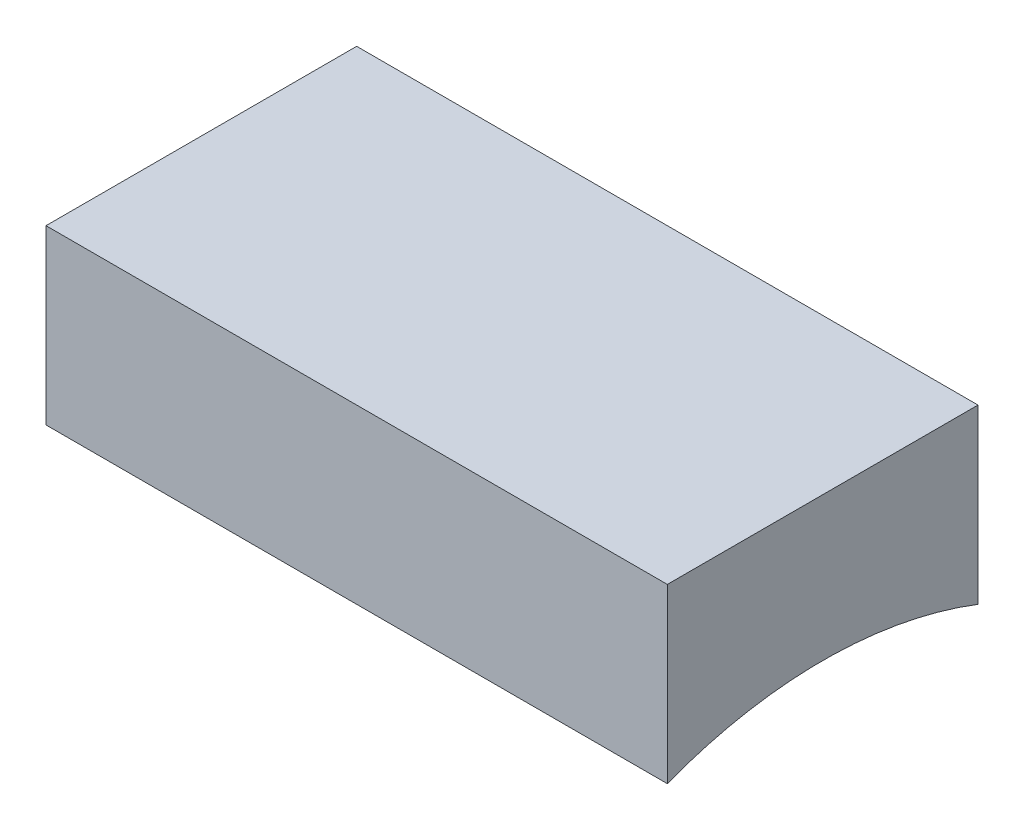
SolidWorks part; units mm, degrees
ref_plane "Front" through (0, 0, 0) normal (0, 0, 1) x (1, 0, 0)
ref_plane "Top" through (0, 0, 0) normal (0, 1, 0) x (1, 0, 0)
ref_plane "Right" through (0, 0, 0) normal (1, 0, 0) x (0, 0, -1)
sketch "Sketch1" plane through (0, 0, 0) normal (0, 1, 0) x (1, 0, 0)
  line L1 (-9, -4.5) -> (9, -4.5)
  line L2 (-9, -4.5) -> (-9, 4.5)
  line L3 (-9, 4.5) -> (9, 4.5)
  line L4 (9, -4.5) -> (9, 4.5)
  line L5 (-9, -4.5) -> (9, 4.5) construction
  line L6 (-9, 4.5) -> (9, -4.5) construction
  point P0 (0, 0)
  dimension "D1" = 9
  dimension "D2" = 18
extrude "Boss-Extrude1" add sketch "Sketch1" along normal blind 5
sketch "Sketch2" plane through (-9, 0, 0) normal (-1, 0, 0) x (0, 0, 1)
  line L1 (-4.5, 0) -> (4.5, 0)
  arc A0 (-4.5, 0) -> (4.5, 0) centre (0, -11.6619) cw
  dimension "D1" = 12.5
extrude "Cut-Extrude1" cut sketch "Sketch2" against normal through all
sketch "Sketch3" plane through (0, 0, 0) normal (0, 1, 0) x (1, 0, 0)
  line L1 (0, 0) -> (-9, 0) construction
  line L2 (-9, 4.5) -> (-9, -4.5) construction
  line L3 (9, -4.5) -> (9, 4.5) construction
  line L4 (-9, 2.5) -> (5.4, 2.5)
  line L5 (-9, 2.5) -> (-9, -2.5)
  line L6 (-9, -2.5) -> (5.4, -2.5)
  line L7 (7, 0.9) -> (7, -0.9)
  line L8 (-9, 2.5) -> (7, -2.5) construction
  line L9 (-9, -2.5) -> (7, 2.5) construction
  arc A0 (5.4, 2.5) -> (7, 0.9) centre (5.4, 0.9) cw
  arc A1 (5.4, -2.5) -> (7, -0.9) centre (5.4, -0.9) ccw
  point P4 (-1, 0)
  dimension "D3" = 1.6
  dimension "D1" = 5
  dimension "D2" = 2
extrude "Cut-Extrude3" cut sketch "Sketch3" along normal blind 3.6
